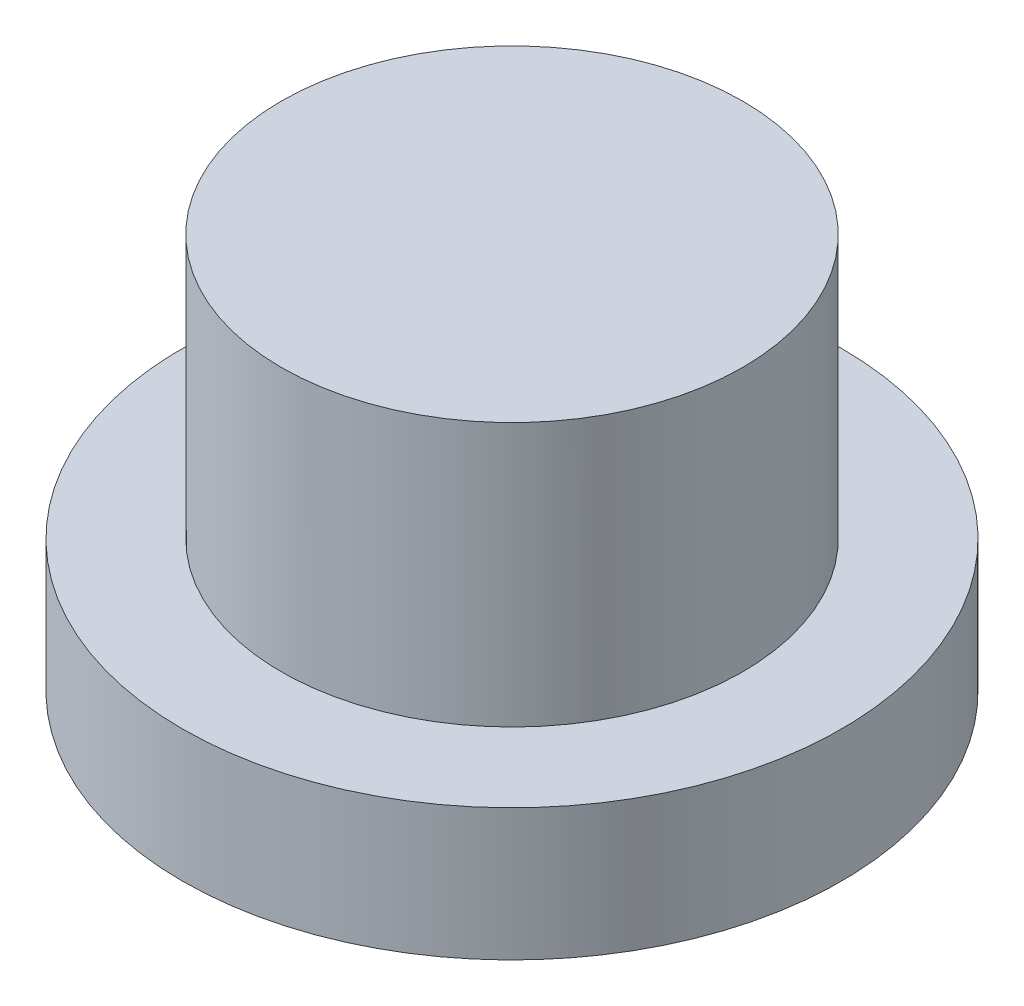
SolidWorks part; units mm, degrees
material "CA"
ref_plane "Front Plane" through (0, 0, 0) normal (0, 0, 1) x (1, 0, 0)
ref_plane "Top Plane" through (0, 0, 0) normal (0, 1, 0) x (1, 0, 0)
ref_plane "Right Plane" through (0, 0, 0) normal (1, 0, 0) x (0, 0, -1)
sketch "Sketch1" plane through (0, 0, 0) normal (0, 1, 0) x (1, 0, 0)
  circle A0 centre (0, 0) radius 2.55
  circle A1 centre (0, 0) radius 3.5
  dimension "D1" = 5.1
  dimension "D2" = 7
extrude "Boss-Extrude1" add sketch "Sketch1" along normal blind 4
sketch "Sketch2" plane through (0, 4, 0) normal (0, 1, 0) x (1, 0, 0)
  circle A0 centre (0, 0) radius 3.5
extrude "Boss-Extrude2" add sketch "Sketch2" along normal blind 2
sketch "Sketch4" plane through (0, 0, 0) normal (0, -1, 0) x (-1, 0, 0)
  circle A0 centre (0, 0) radius 3.5
  circle A1 centre (0, 0) radius 5
  dimension "D1" = 10
extrude "Boss-Extrude3" add sketch "Sketch4" against normal blind 2
